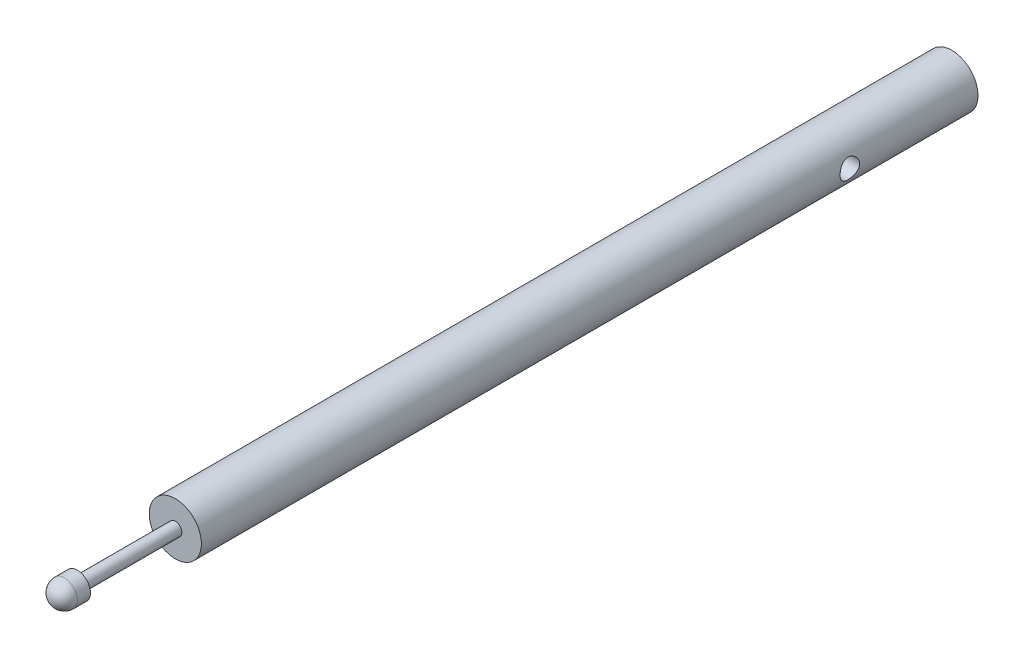
SolidWorks part; units mm, degrees
ref_plane "Płaszczyzna przednia" through (0, 0, 0) normal (0, 0, 1) x (1, 0, 0)
ref_plane "Płaszczyzna górna" through (0, 0, 0) normal (0, 1, 0) x (1, 0, 0)
ref_plane "Płaszczyzna prawa" through (0, 0, 0) normal (1, 0, 0) x (0, 0, -1)
sketch "Szkic1" plane through (0, 0, 0) normal (0, 0, 1) x (1, 0, 0)
  circle A0 centre (0, 0) radius 4
extrude "Dodanie-wyciągnięcie1" add sketch "Szkic1" along normal blind 119
sketch "Szkic2" plane through (0, 0, 0) normal (1, 0, 0) x (0, 0, -1)
  circle A0 centre (-19.6359, 0) radius 1.5
extrude "Wytnij-wyciągnięcie1" cut sketch "Szkic2" against normal up to next and the other way through all
sketch "Szkic3" plane through (0, 0, 119) normal (0, 0, 1) x (1, 0, 0)
  circle A0 centre (0, 0) radius 1
extrude "Dodanie-wyciągnięcie2" add sketch "Szkic3" along normal blind 15
sketch "Szkic4" plane through (0, 0, 134) normal (0, 0, 1) x (1, 0, 0)
  circle A0 centre (0, 0) radius 2
extrude "Dodanie-wyciągnięcie3" add sketch "Szkic4" along normal blind 4
fillet "Zaokrąglenie1" radius 2 1 edges at (2, 0, 138)
